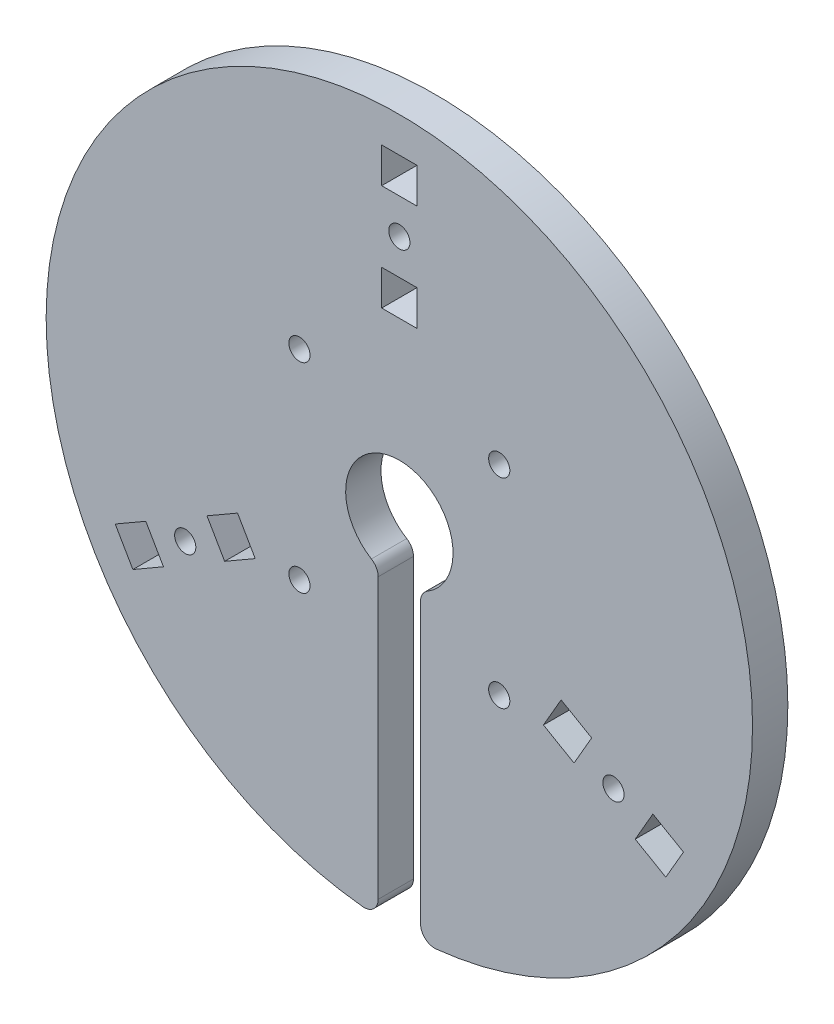
SolidWorks part; units mm, degrees
ref_plane "Plan de face" through (0, 0, 0) normal (0, 0, 1) x (1, 0, 0)
ref_plane "Plan de dessus" through (0, 0, 0) normal (0, 1, 0) x (1, 0, 0)
ref_plane "Plan de droite" through (0, 0, 0) normal (1, 0, 0) x (0, 0, -1)
sketch "Esquisse1" plane through (0, 0, 0) normal (0, 0, 1) x (1, 0, 0)
  line L0 (0, 0) -> (0, 31.2189) construction
  line L1 (0, 0) -> (37.7317, 0) construction
  line L2 (-3, 28.2406) -> (-3, -24.6241) construction
  line L3 (3, -24.6241) -> (3, 28.2406) construction
  line L4 (37.7317, 2.5) -> (-32.0453, 2.5) construction
  line L5 (-32.0453, -2.5) -> (37.7317, -2.5) construction
  line L6 (-3, -6.9828) -> (-3, -49.9099)
  line L7 (3, -49.9099) -> (3, -6.9828)
  line L8 (0, 0) -> (-43.3013, -25) construction
  line L9 (0, 0) -> (43.3013, -25) construction
  line L18 (0, 0) -> (32.7248, 32.7248) construction
  line L19 (0, 0) -> (-39.0036, 39.0036) construction
  circle A0 centre (0, 0) radius 7.6 construction
  circle A1 centre (0, 0) radius 50 construction
  arc A2 (-3, -6.9828) -> (3, -6.9828) centre (0, 0) cw
  arc A3 (-3, -49.9099) -> (3, -49.9099) centre (0, 0) cw
  circle A4 centre (0, 0) radius 35 construction
  circle A5 centre (0, 0) radius 20 construction
  circle A6 centre (14.1421, 14.1421) radius 1.5
  circle A7 centre (14.1421, -14.1421) radius 1.5
  circle A8 centre (-14.1421, 14.1421) radius 1.5
  circle A9 centre (-14.1421, -14.1421) radius 1.5
  line B0 (0, 30) -> (0, 40) construction
  line B1 (-2.5, 30) -> (-2.5, 25)
  line B2 (-2.5, 30) -> (2.5, 30)
  line B3 (2.5, 30) -> (2.5, 25)
  line B4 (-2.5, 25) -> (2.5, 25)
  line B5 (-2.5, 40) -> (-2.5, 45)
  line B6 (-2.5, 40) -> (2.5, 40)
  line B7 (2.5, 40) -> (2.5, 45)
  line B8 (-2.5, 45) -> (2.5, 45)
  circle B9 centre (0, 35) radius 1.5
  line B10 (-34.641, -20) -> (-25.9808, -15) construction
  line B11 (-35.891, -17.8349) -> (-40.2211, -20.3349)
  line B12 (-35.891, -17.8349) -> (-33.391, -22.1651)
  line B13 (-33.391, -22.1651) -> (-37.7211, -24.6651)
  line B14 (-40.2211, -20.3349) -> (-37.7211, -24.6651)
  line B15 (-27.2308, -12.8349) -> (-22.9006, -10.3349)
  line B16 (-27.2308, -12.8349) -> (-24.7308, -17.1651)
  line B17 (-24.7308, -17.1651) -> (-20.4006, -14.6651)
  line B18 (-22.9006, -10.3349) -> (-20.4006, -14.6651)
  circle B19 centre (-30.3109, -17.5) radius 1.5
  line B20 (25.9808, -15) -> (34.641, -20) construction
  line B21 (27.2308, -12.8349) -> (22.9006, -10.3349)
  line B22 (27.2308, -12.8349) -> (24.7308, -17.1651)
  line B23 (24.7308, -17.1651) -> (20.4006, -14.6651)
  line B24 (22.9006, -10.3349) -> (20.4006, -14.6651)
  line B25 (35.891, -17.8349) -> (40.2211, -20.3349)
  line B26 (35.891, -17.8349) -> (33.391, -22.1651)
  line B27 (33.391, -22.1651) -> (37.7211, -24.6651)
  line B28 (40.2211, -20.3349) -> (37.7211, -24.6651)
  circle B29 centre (30.3109, -17.5) radius 1.5
  dimension "D1" = 15.2
  dimension "D2" = 100
  dimension "D5" = 70
  dimension "D7" = 40
  dimension "D8" = 3
  dimension "D3" = 6
  dimension "D4" = 5
  dimension "D6" = 45
  dimension "D9" = 120
  dimension "D10" = 120
sketch_block_instance "Trou M3 plots 5mm-1"
sketch_block "Trou M3 plots 5mm" parameters "D2"=3, "D1"=5, "D3"=5, "D4"=10
sketch_block_instance "Trou M3 plots 5mm-2"
sketch_block_instance "Trou M3 plots 5mm-5"
extrude "Boss.-Extru.1" add sketch "Esquisse1" along normal blind 5
fillet "Fillet1" radius 2 4 edges at (-3, -6.9828, 2.5) (3, -6.9828, 2.5) (3, -49.9099, 2.5) (-3, -49.9099, 2.5)
